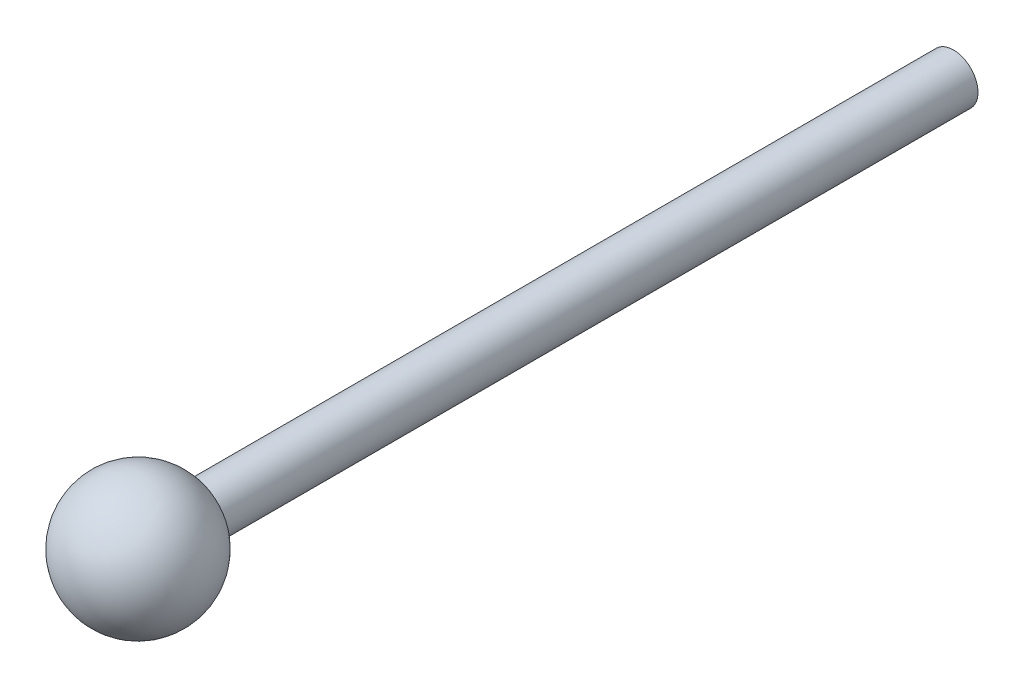
SolidWorks part; units mm, degrees
ref_plane "Front" through (0, 0, 0) normal (0, 0, 1) x (1, 0, 0)
ref_plane "Top" through (0, 0, 0) normal (0, 1, 0) x (1, 0, 0)
ref_plane "Right" through (0, 0, 0) normal (1, 0, 0) x (0, 0, -1)
sketch "Sketch1" plane through (0, 0, 0) normal (0, 0, 1) x (1, 0, 0)
  circle A0 centre (0, 0) radius 7.5
  dimension "D1" = 15
extrude "Base-Extrude" add sketch "Sketch1" against normal blind 250
sketch "Sketch5" plane through (0, 0, 0) normal (0, 0, 1) x (1, 0, 0)
  line L0 (0, 20) -> (0, -10.8337) construction
  line L1 (0, 20) -> (0, -20)
  arc A0 (0, 20) -> (0, -20) centre (0, 0) cw
  dimension "D1" = 20
revolve "Boss-Revolve1" add sketch "Sketch5" angle 360 about L0
